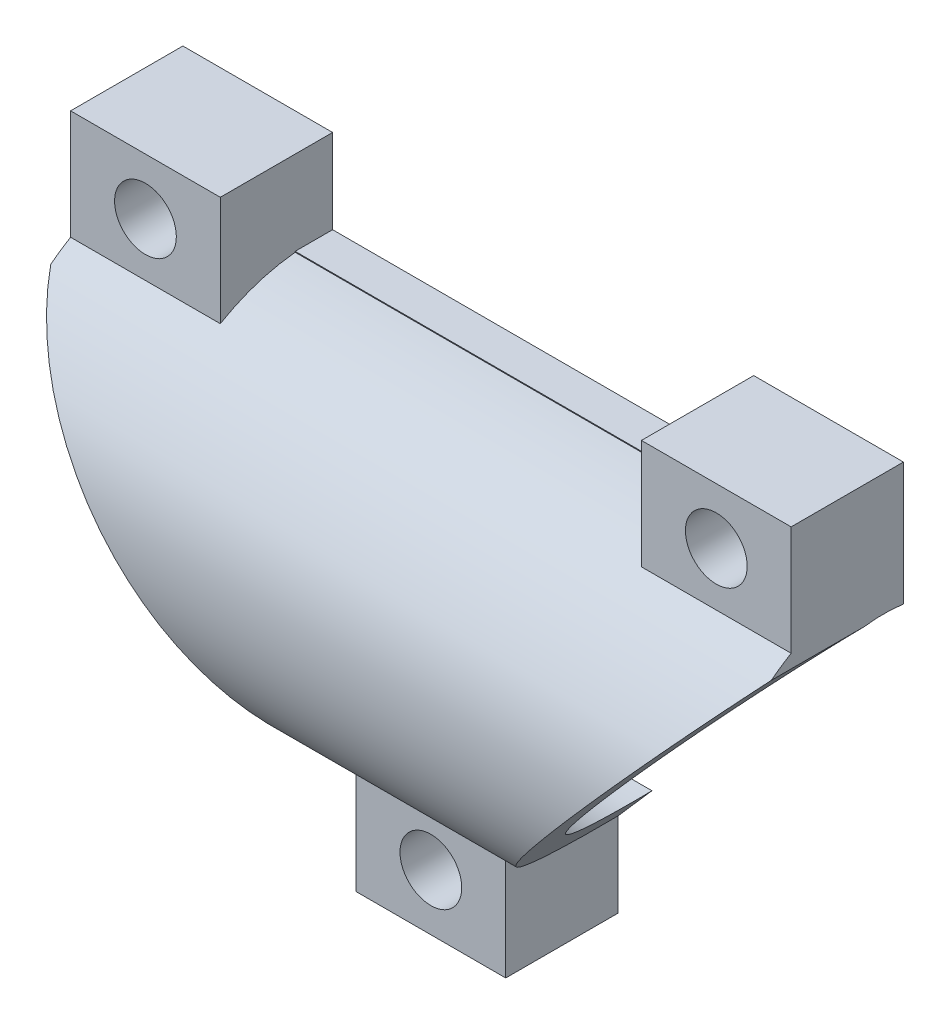
SolidWorks part; units mm, degrees
ref_plane "Přední rovina" through (0, 0, 0) normal (0, 0, 1) x (1, 0, 0)
ref_plane "Horní rovina" through (0, 0, 0) normal (0, 1, 0) x (1, 0, 0)
ref_plane "Pravá rovina" through (0, 0, 0) normal (1, 0, 0) x (0, 0, -1)
sketch "Skica1" plane through (0, 0, 0) normal (0, 0, 1) x (1, 0, 0)
  line L0 (19.25, 35.5) -> (19.25, 33.4285)
  line L1 (-19.25, 40) -> (-11.25, 40)
  line L2 (-19.25, 40) -> (-19.25, 35.5)
  line L4 (-11.25, 40) -> (-11.25, 35.5)
  line L5 (19.25, 40) -> (11.25, 40)
  line L6 (19.25, 40) -> (19.25, 35.5)
  line L8 (11.25, 40) -> (11.25, 35.5)
  line L9 (4, 11.5) -> (-4, 11.5)
  line L10 (4, 11.5) -> (4, 16)
  line L12 (-4, 11.5) -> (-4, 16)
  line L13 (20, 33.4285) -> (-20, 33.4285) construction
  line L14 (19.25, 33.4285) -> (4, 16)
  line L15 (-19.25, 35.5) -> (-19.25, 33.4281)
  line L16 (20, 33.403) -> (-20, 33.4285) construction
  line L17 (-19.25, 33.4281) -> (-4, 16)
  line L18 (11.25, 35.5) -> (-11.25, 35.5)
  circle A0 centre (-15.25, 37) radius 1.65
  circle A1 centre (15.25, 37) radius 1.65
  circle A2 centre (0, 14.5) radius 1.65
extrude "Přidat vysunutím1" add sketch "Skica1" along normal blind 2
sketch "Skica2" plane through (-11.25, 0, 0) normal (1, 0, 0) x (0, 0, -1)
  line L0 (-2, 35.4536) -> (-2, 33.4416)
  line L3 (-2, 18.0584) -> (-2, 16.0464)
  arc A0 (-2, 33.4416) -> (-2, 18.0584) centre (-1.05, 25.75) ccw
  arc A1 (-2, 35.4536) -> (-2, 16.0464) centre (-1.05, 25.75) ccw
  circle A2 centre (-1.05, 25.75) radius 9.75 construction
  circle A3 centre (-1.05, 25.75) radius 7.75 construction
  dimension "D1" = 2
extrude "Přidat vysunutím3" add sketch "Skica2" along normal up to surface and the other way up to surface up to face at (11.625, 24.7143, 1) other way up to face at (-11.625, 24.714, 1)
sketch "Skica3" plane through (-11.25, 0, 0) normal (1, 0, 0) x (0, 0, -1)
  circle A0 centre (-1.05, 25.75) radius 7.75
extrude "Odebrat vysunutím1" cut sketch "Skica3" against normal mid plane 100
sketch "Skica5" plane through (0, 0, 0) normal (0, 0, -1) x (-1, 0, 0)
  line L0 (4, 16) -> (13.3711, 26.7095)
  line L1 (19.25, 40) -> (24.9575, 40)
  line L2 (19.25, 40) -> (19.25, 28.2509)
  line L3 (19.25, 28.2509) -> (24.9575, 28.2509)
  line L4 (24.9575, 40) -> (24.9575, 28.2509)
  line L5 (-19.25, 40) -> (-23.8156, 40)
  line L6 (-19.25, 40) -> (-19.25, 28.2509)
  line L7 (-19.25, 28.2509) -> (-23.8156, 28.2509)
  line L8 (-23.8156, 40) -> (-23.8156, 28.2509)
  line L9 (11.25, 24.2855) -> (19.2618, 33.4416) construction
  line L10 (13.3711, 26.7095) -> (13.3711, 14.1067)
  line L11 (13.3711, 14.1067) -> (4, 16)
extrude "Odebrat vysunutím2" cut sketch "Skica5" against normal blind 100
sketch "Skica6" plane through (0, 0, 2) normal (0, 0, 1) x (1, 0, 0)
  line L0 (19.25, 33.4285) -> (19.25, 35.4536) construction
  line L1 (4, 11.5) -> (-4, 11.5)
  line L2 (4, 11.5) -> (4, 17.7595)
  line L3 (4, 17.7595) -> (-4, 17.7595)
  line L4 (-4, 11.5) -> (-4, 17.7595)
  line L5 (-19.25, 40) -> (-11.25, 40)
  line L6 (-19.25, 40) -> (-19.25, 33.8521)
  line L7 (-19.25, 33.8521) -> (-11.25, 33.8521)
  line L8 (-11.25, 40) -> (-11.25, 33.8521)
  line L9 (11.25, 40) -> (19.25, 40)
  line L10 (11.25, 40) -> (11.25, 33.8521)
  line L11 (11.25, 33.8521) -> (19.25, 33.8521)
  line L12 (19.25, 40) -> (19.25, 33.8521)
  circle A0 centre (15.25, 37) radius 1.65
  circle A1 centre (-15.25, 37) radius 1.65
  circle A2 centre (0, 14.5) radius 1.65
extrude "Přidat vysunutím4" add sketch "Skica6" along normal blind 4
